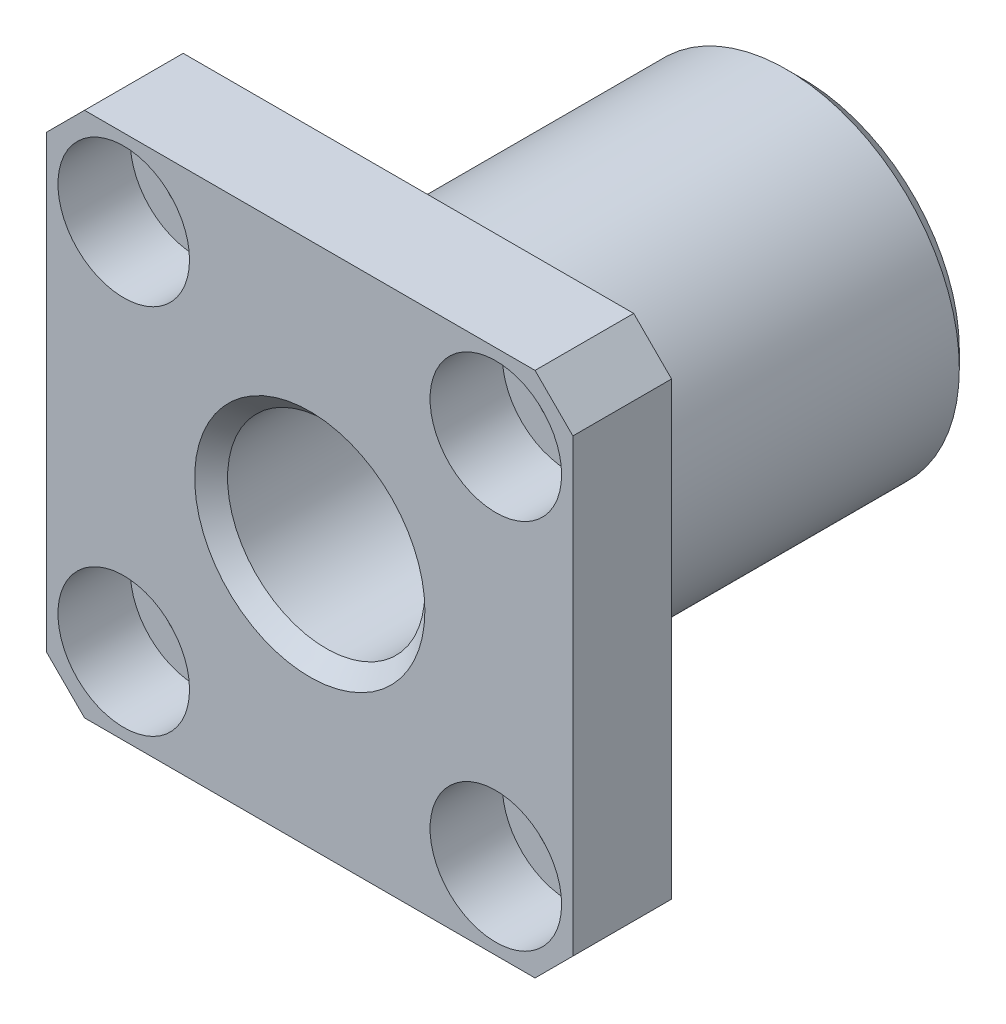
SolidWorks part; units mm, degrees
ref_plane "Front Plane" through (0, 0, 0) normal (0, 0, 1) x (1, 0, 0)
ref_plane "Top Plane" through (0, 0, 0) normal (0, 1, 0) x (1, 0, 0)
ref_plane "Right Plane" through (0, 0, 0) normal (1, 0, 0) x (0, 0, -1)
sketch "Sketch1" plane through (0, 0, 0) normal (0, 0, 1) x (1, 0, 0)
  circle A0 centre (0, 0) radius 10.5
  dimension "D1" = 21
extrude "Boss-Extrude1" add sketch "Sketch1" along normal blind 30
sketch "Sketch2" plane through (0, 0, 30) normal (0, 0, 1) x (1, 0, 0)
  line L1 (-16, -16) -> (16, -16)
  line L2 (-16, -16) -> (-16, 16)
  line L3 (-16, 16) -> (16, 16)
  line L4 (16, -16) -> (16, 16)
  line L5 (-16, -16) -> (16, 16) construction
  line L6 (-16, 16) -> (16, -16) construction
  point P0 (0, 0)
  dimension "D1" = 32
extrude "Boss-Extrude2" add sketch "Sketch2" against normal blind 6
sketch "Sketch4" plane through (0, 0, 30) normal (0, 0, 1) x (1, 0, 0)
  line L0 (0, 16) -> (0, -16) construction
  line L1 (16, 16) -> (-16, 16) construction
  line L2 (-16, -16) -> (16, -16) construction
  line L3 (-16, 16) -> (-16, 13.6985)
  line L4 (-16, 16) -> (-16, -16) construction
  line L5 (-16, 13.6985) -> (-13.6985, 16)
  line L6 (-13.6985, 16) -> (-16, 16)
  line L7 (13.6985, 16) -> (16, 16)
  line L8 (16, 13.6985) -> (13.6985, 16)
  line L9 (16, 16) -> (16, 13.6985)
  line L10 (-16, 0) -> (16, 0) construction
  line L11 (16, -16) -> (16, 16) construction
  line L12 (16, -16) -> (16, -13.6985)
  line L13 (16, -13.6985) -> (13.6985, -16)
  line L14 (13.6985, -16) -> (16, -16)
  line L15 (-13.6985, -16) -> (-16, -16)
  line L16 (-16, -13.6985) -> (-13.6985, -16)
  line L17 (-16, -16) -> (-16, -13.6985)
  dimension "D1" = 42
extrude "Cut-Extrude1" cut sketch "Sketch4" against normal through all
sketch "Sketch5" plane through (0, 0, 30) normal (0, 0, 1) x (1, 0, 0)
  line L0 (0, 0) -> (-14.8492, 14.8492) construction
  line L1 (-16, 13.6985) -> (-13.6985, 16) construction
  circle A0 centre (0, 0) radius 16 construction
  point P6 (-11.3137, 11.3137)
  point P10 (11.3137, 11.3137)
  point P11 (11.3137, -11.3137)
  point P12 (-11.3137, -11.3137)
  point P13 (0, 0)
  dimension "D1" = 32
  dimension "D2" = 4
hole_wizard "CBORE for M4 Hex Socket Head Cap Screw1" positions "Sketch6" profile "Sketch7" counterbore size "M4" standard "ISO"
sketch "Sketch6" plane through (0, 0, 30) normal (0, 0, 1) x (1, 0, 0)
  point P0 (-11.3137, 11.3137)
  point P3 (11.3137, 11.3137)
  point P6 (11.3137, -11.3137)
  point P9 (-11.3137, -11.3137)
sketch "Sketch7" plane through (-11.3137, 11.3137, 30) normal (1, 0, 0) x (0, -1, 0)
  line L0 (0, 0) -> (0, 23.3519)
  line L1 (0, 23.3519) -> (2.25, 22)
  line L2 (2.25, 22) -> (2.25, 4.4)
  line L3 (2.25, 4.4) -> (4, 4.4)
  line L4 (4, 4.4) -> (4, 0)
  line L5 (4, 0) -> (0, 0)
  line L10 (0, 23.3519) -> (-2.25, 22) construction
  line L11 (0, -6.35) -> (0, 107.95) construction
  dimension "Hole Dia." = 4.5
  dimension "Hole Depth" = 22
  dimension "C'Bore Dia." = 8
  dimension "C'Bore Depth" = 4.4
  dimension "Drill Angle" = 118
sketch "Sketch8" plane through (0, 0, 30) normal (0, 0, 1) x (1, 0, 0)
  circle A0 centre (0, 0) radius 6
  dimension "D1" = 12
extrude "Cut-Extrude2" cut sketch "Sketch8" against normal through all
chamfer "Chamfer1" distance 1 angle 45 2 edges at (10.5, 0, 0) (6, 0, 30)
